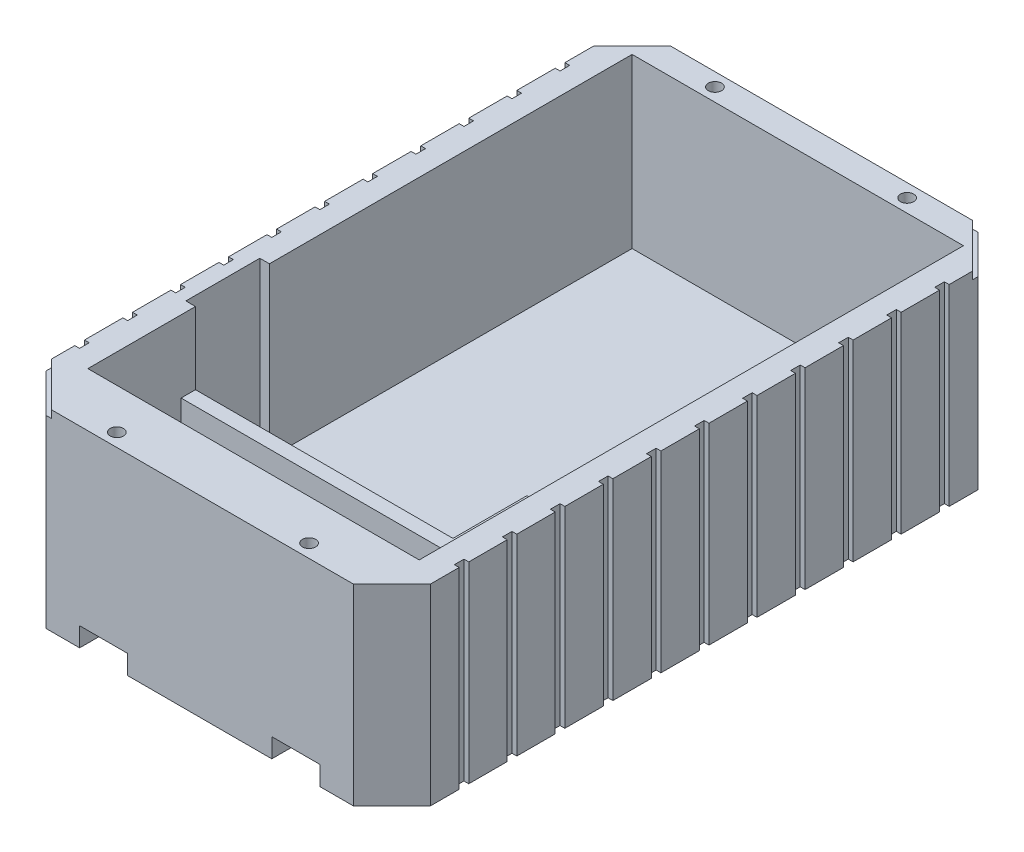
SolidWorks part; units mm, degrees
ref_plane "Front Plane" through (0, 0, 0) normal (0, 0, 1) x (1, 0, 0)
ref_plane "Top Plane" through (0, 0, 0) normal (0, 1, 0) x (1, 0, 0)
ref_plane "Right Plane" through (0, 0, 0) normal (1, 0, 0) x (0, 0, -1)
sketch "Sketch1" plane through (0, 0, 0) normal (0, 1, 0) x (1, 0, 0)
  line L1 (-50.8, -82.55) -> (50.8, -82.55)
  line L2 (-50.8, -82.55) -> (-50.8, 82.55)
  line L3 (-50.8, 82.55) -> (50.8, 82.55)
  line L4 (50.8, -82.55) -> (50.8, 82.55)
  line L5 (-50.8, -82.55) -> (50.8, 82.55) construction
  line L6 (-50.8, 82.55) -> (50.8, -82.55) construction
  point P0 (0, 0)
  dimension "D1" = 101.6
  dimension "D2" = 165.1
extrude "Boss-Extrude1" add sketch "Sketch1" along normal blind 50.8
sketch "Sketch2" plane through (0, 50.8, 0) normal (0, 1, 0) x (1, 0, 0)
  line L0 (-50.8, 82.55) -> (-50.8, -82.55) construction
  line L1 (-52.07, -64.77) -> (-49.53, -64.77)
  line L2 (-52.07, -64.77) -> (-52.07, -62.23)
  line L3 (-52.07, -62.23) -> (-49.53, -62.23)
  line L4 (-49.53, -64.77) -> (-49.53, -62.23)
  line L5 (-52.07, -64.77) -> (-49.53, -62.23) construction
  line L6 (-52.07, -62.23) -> (-49.53, -64.77) construction
  line L7 (50.8, -82.55) -> (50.8, 82.55) construction
  line L8 (52.07, -64.77) -> (49.53, -64.77)
  line L9 (52.07, -64.77) -> (52.07, -62.23)
  line L10 (52.07, -62.23) -> (49.53, -62.23)
  line L11 (49.53, -64.77) -> (49.53, -62.23)
  line L12 (52.07, -64.77) -> (49.53, -62.23) construction
  line L13 (52.07, -62.23) -> (49.53, -64.77) construction
  line L14 (-52.07, -52.07) -> (-49.53, -52.07)
  line L15 (-52.07, -52.07) -> (-52.07, -49.53)
  line L16 (-52.07, -49.53) -> (-49.53, -49.53)
  line L17 (-49.53, -52.07) -> (-49.53, -49.53)
  line L18 (52.07, -52.07) -> (49.53, -52.07)
  line L19 (49.53, -52.07) -> (49.53, -49.53)
  line L20 (52.07, -49.53) -> (49.53, -49.53)
  line L21 (52.07, -52.07) -> (52.07, -49.53)
  line L22 (-52.07, -39.37) -> (-49.53, -39.37)
  line L23 (-52.07, -39.37) -> (-52.07, -36.83)
  line L24 (-52.07, -36.83) -> (-49.53, -36.83)
  line L25 (-49.53, -39.37) -> (-49.53, -36.83)
  line L26 (52.07, -39.37) -> (49.53, -39.37)
  line L27 (49.53, -39.37) -> (49.53, -36.83)
  line L28 (52.07, -36.83) -> (49.53, -36.83)
  line L29 (52.07, -39.37) -> (52.07, -36.83)
  line L30 (-52.07, -26.67) -> (-49.53, -26.67)
  line L31 (-52.07, -26.67) -> (-52.07, -24.13)
  line L32 (-52.07, -24.13) -> (-49.53, -24.13)
  line L33 (-49.53, -26.67) -> (-49.53, -24.13)
  line L34 (52.07, -26.67) -> (49.53, -26.67)
  line L35 (49.53, -26.67) -> (49.53, -24.13)
  line L36 (52.07, -24.13) -> (49.53, -24.13)
  line L37 (52.07, -26.67) -> (52.07, -24.13)
  line L38 (-52.07, -13.97) -> (-49.53, -13.97)
  line L39 (-52.07, -13.97) -> (-52.07, -11.43)
  line L40 (-52.07, -11.43) -> (-49.53, -11.43)
  line L41 (-49.53, -13.97) -> (-49.53, -11.43)
  line L42 (52.07, -13.97) -> (49.53, -13.97)
  line L43 (49.53, -13.97) -> (49.53, -11.43)
  line L44 (52.07, -11.43) -> (49.53, -11.43)
  line L45 (52.07, -13.97) -> (52.07, -11.43)
  line L46 (-52.07, -1.27) -> (-49.53, -1.27)
  line L47 (-52.07, -1.27) -> (-52.07, 1.27)
  line L48 (-52.07, 1.27) -> (-49.53, 1.27)
  line L49 (-49.53, -1.27) -> (-49.53, 1.27)
  line L50 (52.07, -1.27) -> (49.53, -1.27)
  line L51 (49.53, -1.27) -> (49.53, 1.27)
  line L52 (52.07, 1.27) -> (49.53, 1.27)
  line L53 (52.07, -1.27) -> (52.07, 1.27)
  line L54 (-52.07, 11.43) -> (-49.53, 11.43)
  line L55 (-52.07, 11.43) -> (-52.07, 13.97)
  line L56 (-52.07, 13.97) -> (-49.53, 13.97)
  line L57 (-49.53, 11.43) -> (-49.53, 13.97)
  line L58 (52.07, 11.43) -> (49.53, 11.43)
  line L59 (49.53, 11.43) -> (49.53, 13.97)
  line L60 (52.07, 13.97) -> (49.53, 13.97)
  line L61 (52.07, 11.43) -> (52.07, 13.97)
  line L62 (-52.07, 24.13) -> (-49.53, 24.13)
  line L63 (-52.07, 24.13) -> (-52.07, 26.67)
  line L64 (-52.07, 26.67) -> (-49.53, 26.67)
  line L65 (-49.53, 24.13) -> (-49.53, 26.67)
  line L66 (52.07, 24.13) -> (49.53, 24.13)
  line L67 (49.53, 24.13) -> (49.53, 26.67)
  line L68 (52.07, 26.67) -> (49.53, 26.67)
  line L69 (52.07, 24.13) -> (52.07, 26.67)
  line L70 (-52.07, 36.83) -> (-49.53, 36.83)
  line L71 (-52.07, 36.83) -> (-52.07, 39.37)
  line L72 (-52.07, 39.37) -> (-49.53, 39.37)
  line L73 (-49.53, 36.83) -> (-49.53, 39.37)
  line L74 (52.07, 36.83) -> (49.53, 36.83)
  line L75 (49.53, 36.83) -> (49.53, 39.37)
  line L76 (52.07, 39.37) -> (49.53, 39.37)
  line L77 (52.07, 36.83) -> (52.07, 39.37)
  line L78 (-52.07, 49.53) -> (-49.53, 49.53)
  line L79 (-52.07, 49.53) -> (-52.07, 52.07)
  line L80 (-52.07, 52.07) -> (-49.53, 52.07)
  line L81 (-49.53, 49.53) -> (-49.53, 52.07)
  line L82 (52.07, 49.53) -> (49.53, 49.53)
  line L83 (49.53, 49.53) -> (49.53, 52.07)
  line L84 (52.07, 52.07) -> (49.53, 52.07)
  line L85 (52.07, 49.53) -> (52.07, 52.07)
  line L86 (-52.07, 62.23) -> (-49.53, 62.23)
  line L87 (-52.07, 62.23) -> (-52.07, 64.77)
  line L88 (-52.07, 64.77) -> (-49.53, 64.77)
  line L89 (-49.53, 62.23) -> (-49.53, 64.77)
  line L90 (52.07, 62.23) -> (49.53, 62.23)
  line L91 (49.53, 62.23) -> (49.53, 64.77)
  line L92 (52.07, 64.77) -> (49.53, 64.77)
  line L93 (52.07, 62.23) -> (52.07, 64.77)
  point P0 (-50.8, -63.5)
  point P7 (50.8, -63.5)
  dimension "D1" = 11
  dimension "D2" = 10.16
  dimension "D3" = 17.78
extrude "Cut-Extrude1" cut sketch "Sketch2" against normal through all
chamfer "Chamfer1" distance 10.16 angle 45 4 edges at (-50.8, 25.4, -82.55) (-50.8, 25.4, 82.55) (50.8, 25.4, 82.55) (50.8, 25.4, -82.55)
sketch "Sketch3" plane through (0, 50.8, 0) normal (0, 1, 0) x (1, 0, 0)
  line L0 (50.8, 64.77) -> (50.8, 72.39) construction
  line L1 (-43.8, -68.326) -> (43.8, -68.326)
  line L2 (-43.8, -68.326) -> (-43.8, 75.55)
  line L3 (-43.8, 75.55) -> (43.8, 75.55)
  line L4 (43.8, -68.326) -> (43.8, 75.55)
  line L5 (-43.8, -68.326) -> (43.8, 75.55) construction
  line L6 (-43.8, 75.55) -> (43.8, -68.326) construction
  line L7 (-40.64, -82.55) -> (40.64, -82.55) construction
  line L10 (40.64, 82.55) -> (-40.64, 82.55) construction
  dimension "D1" = 7
  dimension "D2" = 14.224
  dimension "D3" = 7
extrude "Cut-Extrude2" cut sketch "Sketch3" against normal blind 44.45
sketch "Sketch4" plane through (0, 50.8, 0) normal (0, 1, 0) x (1, 0, 0)
  line L2 (45.0129, 76.7629) -> (50.8, 70.9758)
  line L3 (50.8, 64.77) -> (50.8, 72.39) construction
  line L4 (50.8, 70.9758) -> (50.8, 72.39)
  line L5 (50.8, 72.39) -> (40.64, 82.55)
  line L6 (45.0129, 76.7629) -> (39.2258, 82.55)
  line L7 (40.64, 82.55) -> (-40.64, 82.55) construction
  line L8 (39.2258, 82.55) -> (40.64, 82.55)
  line L10 (-45.0129, -76.7629) -> (-50.8, -70.9758)
  line L11 (-50.8, -64.77) -> (-50.8, -72.39) construction
  line L12 (-50.8, -70.9758) -> (-50.8, -72.39)
  line L13 (-50.8, -72.39) -> (-40.64, -82.55)
  line L14 (-45.0129, -76.7629) -> (-39.2258, -82.55)
  line L15 (-40.64, -82.55) -> (40.64, -82.55) construction
  line L16 (-39.2258, -82.55) -> (-40.64, -82.55)
extrude "Cut-Extrude3" cut sketch "Sketch4" against normal blind 2
sketch "Sketch5" plane through (0, 50.8, 0) normal (0, 1, 0) x (1, 0, 0)
  line L0 (-50.8, -64.77) -> (-50.8, -70.9758) construction
  line L1 (50.8, -72.39) -> (50.8, -64.77) construction
  line L2 (50.8, 64.77) -> (50.8, 70.9758) construction
  line L3 (-50.8, 72.39) -> (-50.8, 64.77) construction
  line L4 (39.2258, 82.55) -> (-40.64, 82.55) construction
  line L5 (-39.2258, -82.55) -> (40.64, -82.55) construction
  circle A0 centre (-25.4, -79.05) radius 1.75
  circle A1 centre (25.4, -79.05) radius 1.75
  circle A2 centre (25.4, 79.05) radius 1.75
  circle A3 centre (-25.4, 79.05) radius 1.75
  dimension "D1" = 3.5
  dimension "D2" = 3.5
  dimension "D3" = 3.5
  dimension "D4" = 3.5
  dimension "D5" = 25.4
  dimension "D6" = 25.4
  dimension "D7" = 25.4
  dimension "D8" = 25.4
  dimension "D9" = 3.5
  dimension "D10" = 3.5
  dimension "D11" = 3.5
  dimension "D12" = 3.5
extrude "Cut-Extrude4" cut sketch "Sketch5" against normal through all
sketch "Sketch6" plane through (0, 0, 0) normal (0, -1, 0) x (1, 0, 0)
  line L0 (-40.64, 82.55) -> (40.64, 82.55) construction
  line L1 (-31.75, 75.55) -> (-19.05, 75.55)
  line L2 (-31.75, 75.55) -> (-31.75, 82.55)
  line L3 (-31.75, 82.55) -> (-19.05, 82.55)
  line L4 (-19.05, 75.55) -> (-19.05, 82.55)
  line L5 (-31.75, 75.55) -> (-19.05, 82.55) construction
  line L6 (-31.75, 82.55) -> (-19.05, 75.55) construction
  line L7 (40.64, -82.55) -> (-40.64, -82.55) construction
  line L8 (19.05, 75.55) -> (31.75, 75.55)
  line L9 (19.05, 75.55) -> (19.05, 82.55)
  line L10 (19.05, 82.55) -> (31.75, 82.55)
  line L11 (31.75, 75.55) -> (31.75, 82.55)
  line L12 (19.05, 75.55) -> (31.75, 82.55) construction
  line L13 (19.05, 82.55) -> (31.75, 75.55) construction
  line L14 (-31.75, -75.55) -> (-19.05, -75.55)
  line L15 (-31.75, -75.55) -> (-31.75, -82.55)
  line L16 (-31.75, -82.55) -> (-19.05, -82.55)
  line L17 (-19.05, -75.55) -> (-19.05, -82.55)
  line L18 (-31.75, -75.55) -> (-19.05, -82.55) construction
  line L19 (-31.75, -82.55) -> (-19.05, -75.55) construction
  line L21 (19.05, -75.55) -> (31.75, -75.55)
  line L22 (19.05, -75.55) -> (19.05, -82.55)
  line L23 (19.05, -82.55) -> (31.75, -82.55)
  line L24 (31.75, -75.55) -> (31.75, -82.55)
  line L25 (19.05, -75.55) -> (31.75, -82.55) construction
  line L26 (19.05, -82.55) -> (31.75, -75.55) construction
  circle A0 centre (25.4, -79.05) radius 1.75 construction
  circle A2 centre (-25.4, 79.05) radius 1.75 construction
  circle A3 centre (25.4, 79.05) radius 1.75 construction
  point P0 (-25.4, 79.05)
  point P8 (25.4, 79.05)
  point P22 (25.4, -79.05)
  dimension "D1" = 7
  dimension "D2" = 12.7
  dimension "D3" = 0
  dimension "D4" = 12.7
  dimension "D5" = 7
  dimension "D6" = 12.7
  dimension "D7" = 7
  dimension "D8" = 0
  dimension "D9" = 12.7
  dimension "D10" = 7
  dimension "D11" = 0
extrude "Cut-Extrude5" cut sketch "Sketch6" against normal blind 5.08
sketch "Sketch7" plane through (0, 0, 0) normal (0, -1, 0) x (1, 0, 0)
  line L0 (-19.05, 82.55) -> (19.05, 82.55) construction
  line L3 (-7.747, 64.77) -> (7.747, 64.77)
  line L4 (-7.747, 64.77) -> (-7.747, 53.34)
  line L5 (-7.747, 53.34) -> (7.747, 53.34)
  line L6 (7.747, 64.77) -> (7.747, 53.34)
  point P0 (0, 64.77)
  point P8 (0, 82.55)
  dimension "D1" = 0
  dimension "D2" = 15.494
  dimension "D3" = 11.43
  dimension "D4" = 17.78
extrude "Cut-Extrude6" cut sketch "Sketch7" against normal through all
sketch "Sketch9" plane through (0, 0, 68.326) normal (0, 0, -1) x (-1, 0, 0)
  circle A0 centre (-9.934, 31.651) radius 1.75
  circle A1 centre (10.188, 31.651) radius 1.75
  circle A2 centre (10.188, 14.196) radius 1.75
  circle A3 centre (-9.934, 14.069) radius 1.75
  dimension "D4" = 3.5
  dimension "D5" = 3.5
  dimension "D6" = 3.5
  dimension "D7" = 3.5
extrude "Cut-Extrude7" cut sketch "Sketch9" against normal blind 5.08
sketch "Sketch10" plane through (0, 6.35, 0) normal (0, 1, 0) x (1, 0, 0)
  line L0 (-43.8, 75.55) -> (-43.8, -68.326) construction
  line L1 (-43.8, -39.878) -> (24.272, -39.878)
  line L2 (-43.8, -39.878) -> (-43.8, -20.32)
  line L3 (-43.8, -20.32) -> (24.272, -20.32)
  line L4 (24.272, -39.878) -> (24.272, -20.32)
  line L5 (-43.8, -68.326) -> (43.8, -68.326) construction
  dimension "D1" = 28.448
  dimension "D2" = 19.558
  dimension "D3" = 68.072
extrude "Boss-Extrude2" add sketch "Sketch10" along normal blind 2.54
sketch "Sketch11" plane through (0, 6.35, 0) normal (0, 1, 0) x (1, 0, 0)
  line L0 (-43.8, -43.688) -> (28.082, -43.688)
  line L1 (-43.8, -39.878) -> (-43.8, -68.326) construction
  line L2 (24.272, -20.32) -> (28.082, -20.32)
  line L3 (28.082, -20.32) -> (28.082, -43.688)
  line L4 (24.272, -39.878) -> (24.272, -20.32) construction
  line L5 (-43.8, -39.878) -> (24.272, -39.878) construction
  line L6 (-43.8, -43.688) -> (-43.8, -39.878)
  line L7 (-43.8, -39.878) -> (24.272, -39.878)
  line L8 (24.272, -39.878) -> (24.272, -20.32)
  dimension "D1" = 3.81
  dimension "D2" = 3.81
extrude "Boss-Extrude3" add sketch "Sketch11" along normal blind 25.4
sketch "Sketch12" plane through (-43.8, 0, 0) normal (1, 0, 0) x (0, 0, -1)
  line L0 (-39.878, 8.89) -> (-39.878, 50.8)
  line L1 (75.55, 50.8) -> (-68.326, 50.8) construction
  line L2 (-39.878, 8.89) -> (-20.32, 8.89)
  line L3 (-20.32, 8.89) -> (-20.32, 50.8)
  line L4 (-20.32, 50.8) -> (-39.878, 50.8)
extrude "Cut-Extrude8" cut sketch "Sketch12" against normal blind 2.54
